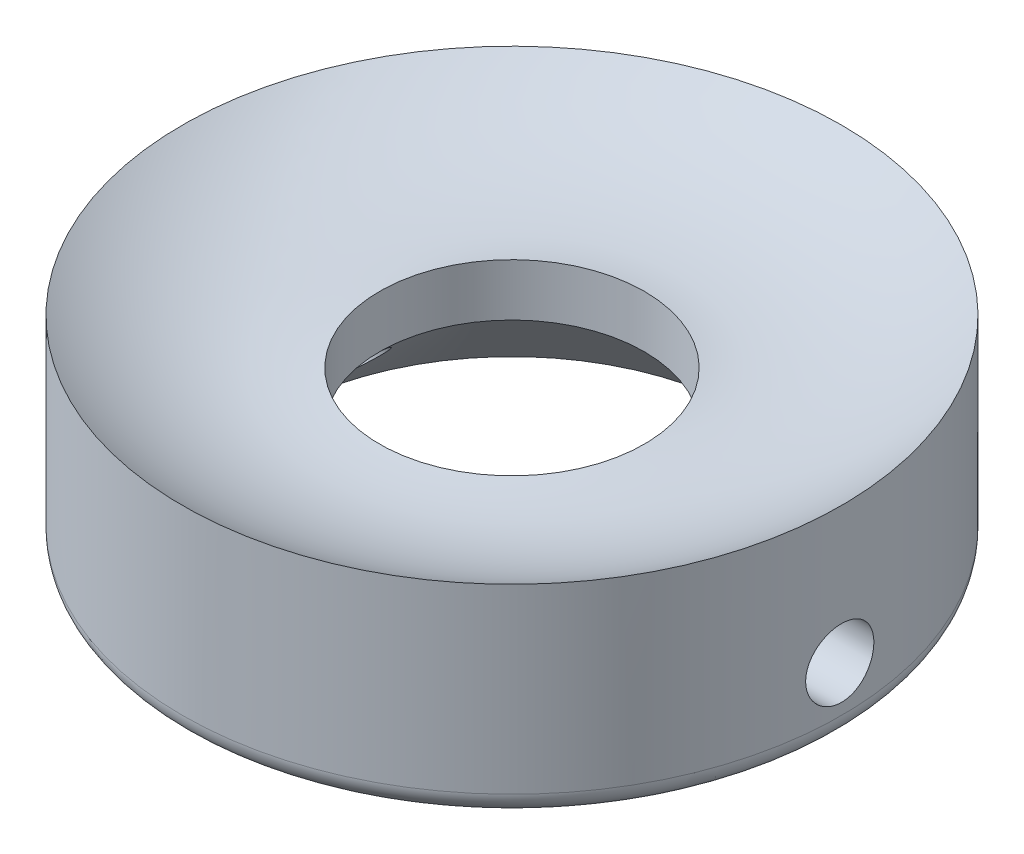
SolidWorks part; units mm, degrees
material "Nylon 101"
ref_plane "Front Plane" through (0, 0, 0) normal (0, 0, 1) x (1, 0, 0)
ref_plane "Top Plane" through (0, 0, 0) normal (0, 1, 0) x (1, 0, 0)
ref_plane "Right Plane" through (0, 0, 0) normal (1, 0, 0) x (0, 0, -1)
sketch "Sketch1" plane through (0, 0, 0) normal (0, 1, 0) x (1, 0, 0)
  circle A0 centre (0, 0) radius 36.83
extrude "Boss-Extrude1" add sketch "Sketch1" along normal blind 22.86
fillet "Fillet1" radius 2.54 1 edges at (0, 0, 36.83)
sketch "Sketch2" plane through (0, 0, 0) normal (0, 1, 0) x (1, 0, 0)
  circle A0 centre (0, 0) radius 26.67
  dimension "D1" = 53.34
ref_plane "Plane1" through (0, 11.938, 0) normal (0, 1, 0) x (1, 0, 0)
sketch "Sketch3" plane through (0, 11.938, 0) normal (0, 1, 0) x (1, 0, 0)
  circle A0 centre (0, 0) radius 14.7955
  dimension "D1" = 29.591
loft "Cut-Loft1" cut profiles "Sketch2", "Sketch3"
sketch "Sketch4" plane through (0, 11.938, 0) normal (0, -1, 0) x (1, 0, 0)
  circle A0 centre (0, 0) radius 14.7955 construction
  circle A1 centre (0, 0) radius 14.7955
extrude "Cut-Extrude1" cut sketch "Sketch4" against normal blind 76.2
ref_plane "Plane2" through (0, 16.51, 0) normal (0, 1, 0) x (1, 0, 0)
ref_plane "Plane3" through (0, 0, 36.83) normal (0, 0, 1) x (1, 0, 0)
sketch "Sketch17" plane through (0, 0, 0) normal (1, 0, 0) x (0, 0, -1)
  line L0 (0, 0) -> (0, 17.78) construction
  line L1 (36.83, 22.86) -> (-36.83, 22.86) construction
  line L3 (36.83, 22.86) -> (14.7955, 22.86)
  line L4 (14.7955, 22.86) -> (14.7955, 17.78)
  arc A0 (36.83, 22.86) -> (14.7955, 17.78) centre (19.1475, 49.2303) cw
  dimension "D2" = 31.75
  dimension "D1" = 17.78
  dimension "D3" = 14.7955
revolve "Cut-Revolve1" cut sketch "Sketch17" angle 360 about L0
sketch "Sketch18" plane through (0, 0, 0) normal (0, -1, 0) x (1, 0, 0)
  line L0 (0, 0) -> (0, 30.4312) construction
  line L1 (30.4312, 0) -> (0, 0) construction
  line L2 (0, 0) -> (0, -30.4312) construction
  line L3 (0, 0) -> (-30.4312, 0) construction
  arc A0 (0, 30.4312) -> (30.4312, 0) centre (0, 0) cw construction
  circle A1 centre (0, 30.4312) radius 3.175
  circle A3 centre (0, -30.4312) radius 3.175
  dimension "D1" = 30.4312
  dimension "D3" = 30.4312
  dimension "D4" = 30.4312
  dimension "D5" = 30.4312
extrude "Cut-Extrude2" cut sketch "Sketch18" against normal blind 6.35
sketch "Sketch19" plane through (0, 0, 0) normal (0, -1, 0) x (1, 0, 0)
  line L0 (0, -30.4312) -> (3.175, -30.4312) construction
  line L1 (3.175, -30.4312) -> (4.445, -30.4312) construction
  line L3 (4.2597, -31.7012) -> (2.9099, -31.7012)
  line L4 (4.2597, -29.1612) -> (2.9099, -29.1612)
  circle A0 centre (0, -30.4312) radius 3.175 construction
  arc A1 (4.2597, -31.7012) -> (4.2597, -29.1612) centre (0, -30.4312) ccw
  arc A2 (2.9099, -31.7012) -> (2.9099, -29.1612) centre (0, -30.4312) ccw
  dimension "D1" = 1.27
  dimension "D2" = 2.54
extrude "Cut-Extrude3" cut sketch "Sketch19" against normal up to surface (6.35 mm away) up to face at (0, 6.35, -33.6062)
sketch "Sketch20" plane through (0, 6.35, 0) normal (0, -1, 0) x (1, 0, 0)
  line L0 (-1.27, -34.6909) -> (-1.27, -33.3411)
  line L1 (2.9099, -31.7012) -> (4.2597, -31.7012) construction
  line L2 (2.9099, -31.7012) -> (4.2597, -31.7012)
  arc A0 (-1.27, -34.6909) -> (4.2597, -31.7012) centre (0, -30.4312) ccw
  arc A1 (2.9099, -29.1612) -> (2.9099, -31.7012) centre (0, -30.4312) ccw construction
  arc A2 (-1.27, -33.3411) -> (2.9099, -31.7012) centre (0, -30.4312) ccw
  point P15 (0, -30.4312)
  dimension "D1" = 4.445
extrude "Cut-Extrude4" cut sketch "Sketch20" along normal blind 2.54
pattern_circular "CirPattern1" count 2 over 360 about axis through (0, 0, 0) along (0, 1, 0) of "Cut-Extrude3", "Cut-Extrude4"
sketch "Sketch21" plane through (0, 0, 0) normal (0, -1, 0) x (1, 0, 0)
  line L0 (34.29, 0) -> (0, 0) construction
  line L1 (0, 0) -> (0, -34.29) construction
  line L2 (30.3335, 30.3335) -> (0, 0) construction
  arc A0 (0, 34.29) -> (-34.29, 0) centre (0, 0) ccw
  arc A1 (34.29, 0) -> (0, -34.29) centre (0, 0) cw
  point P1 (24.2467, -24.2467)
  point P9 (-24.2467, 24.2467)
  dimension "D1" = 45
sketch "Sketch22" plane through (0, 0, 0) normal (1, 0, 0) x (0, 0, -1)
  line L0 (36.83, 22.86) -> (36.83, 0) construction
  line L1 (36.83, 22.86) -> (-36.83, 22.86) construction
  circle A0 centre (0, 7.62) radius 3.81
  dimension "D1" = 15.24
extrude "Cut-Extrude5" cut sketch "Sketch22" against normal through all both and the other way through all
